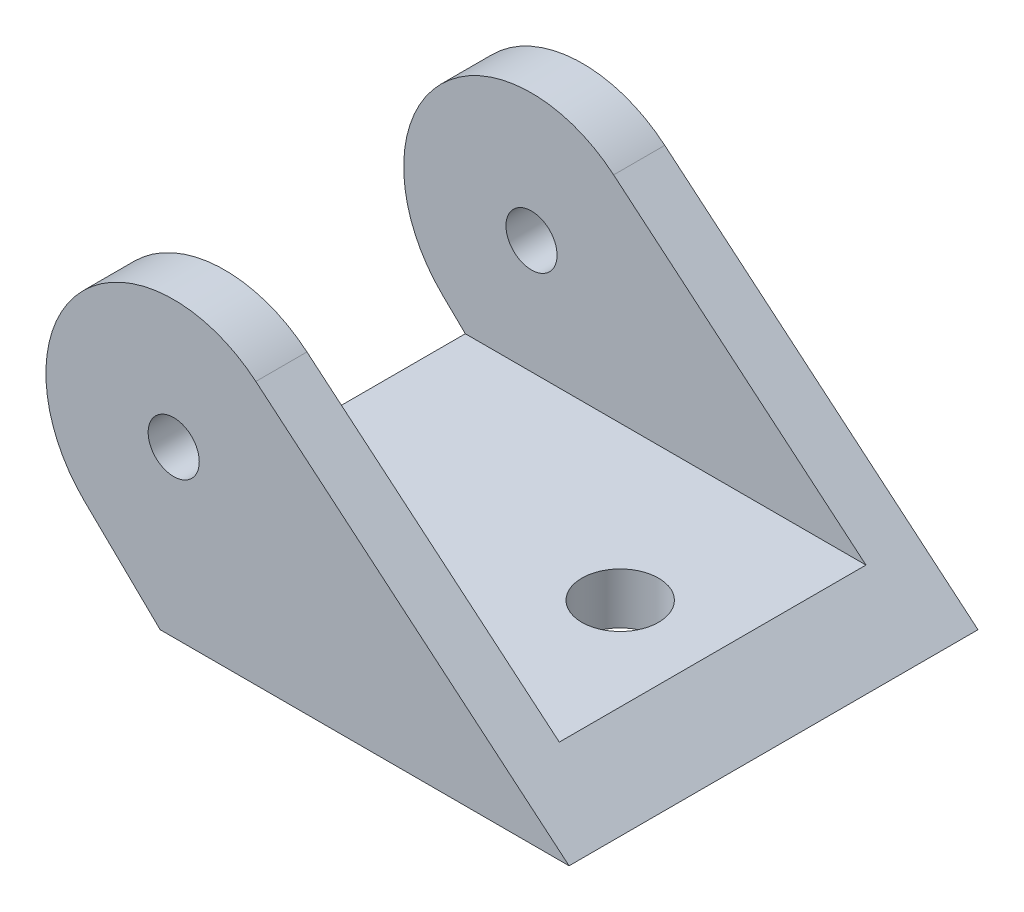
SolidWorks part; units mm, degrees
ref_plane "Front Plane" through (0, 0, 0) normal (0, 0, 1) x (1, 0, 0)
ref_plane "Top Plane" through (0, 0, 0) normal (0, 1, 0) x (1, 0, 0)
ref_plane "Right Plane" through (0, 0, 0) normal (1, 0, 0) x (0, 0, -1)
sketch "Sketch1" plane through (0, 0, 0) normal (0, 0, 1) x (1, 0, 0)
  line L0 (0, 0) -> (-9.3765, 9.1016)
  line L1 (0, 0) -> (50.8, 0)
  line L2 (50.8, 0) -> (11.8849, 32.6536)
  arc A0 (11.8849, 32.6536) -> (-9.3765, 9.1016) centre (1.6807, 20.4927) ccw
  circle A1 centre (1.6807, 20.4927) radius 3.175
  dimension "D1" = 50.8
  dimension "D5" = 6.35
  dimension "D4" = 15.875
  dimension "D2" = 50.8
  dimension "D3" = 40
extrude "Boss-Extrude1" add sketch "Sketch1" along normal mid plane 50.8
sketch "Sketch2" plane through (0, 0, 0) normal (0, 1, 0) x (1, 0, 0)
  line L0 (-14.1943, 25.4) -> (-14.1943, -25.4) construction
  line L1 (-14.1943, 19.05) -> (50.8, 19.05)
  line L2 (-14.1943, 19.05) -> (-14.1943, -19.05)
  line L3 (-14.1943, -19.05) -> (50.8, -19.05)
  line L4 (50.8, 19.05) -> (50.8, -19.05)
  line L5 (50.8, -25.4) -> (50.8, 25.4) construction
  line L6 (11.8849, 25.4) -> (-14.1943, 25.4) construction
  line L7 (-14.1943, -25.4) -> (11.8849, -25.4) construction
  dimension "D1" = 6.35
  dimension "D2" = 6.35
extrude "Cut-Extrude1" cut sketch "Sketch2" against normal offset from surface (44.45 mm away) 6.35 from offset 50.8 up to face at (25.4, 0, 0)
sketch "Sketch3" plane through (0, 6.35, 0) normal (0, 1, 0) x (1, 0, 0)
  line L0 (31.75, 0) -> (50.8, 0) construction
  line L1 (50.8, -25.4) -> (50.8, 25.4) construction
  circle A0 centre (31.75, 0) radius 4.7625
  dimension "D1" = 9.525
  dimension "D2" = 19.05
extrude "Cut-Extrude2" cut sketch "Sketch3" against normal through all
